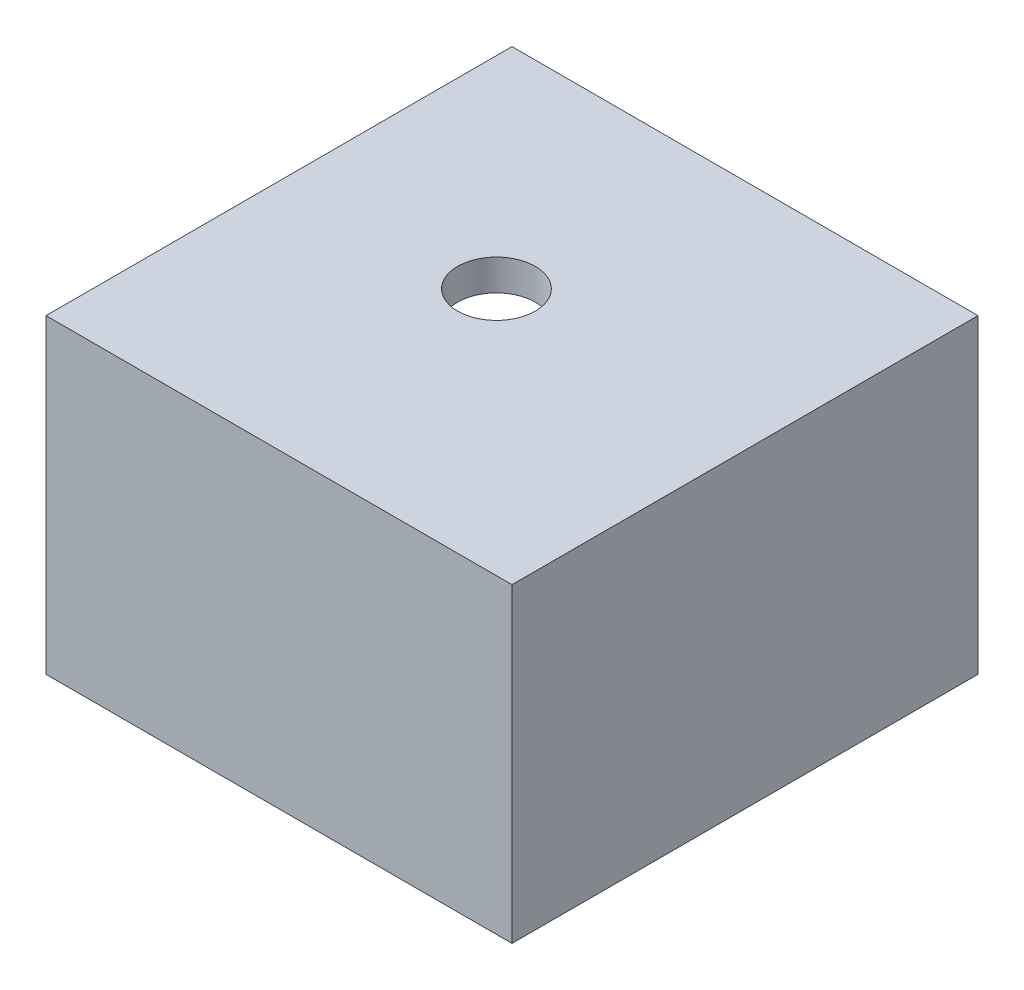
SolidWorks part; units mm, degrees
material "ABS PC"
ref_plane "Front Plane" through (0, 0, 0) normal (0, 0, 1) x (1, 0, 0)
ref_plane "Top Plane" through (0, 0, 0) normal (0, 1, 0) x (1, 0, 0)
ref_plane "Right Plane" through (0, 0, 0) normal (1, 0, 0) x (0, 0, -1)
sketch "Sketch1" plane through (0, 0, 0) normal (0, 1, 0) x (1, 0, 0)
  line L1 (15, -15) -> (-15, -15)
  line L2 (15, -15) -> (15, 15)
  line L3 (15, 15) -> (-15, 15)
  line L4 (-15, -15) -> (-15, 15)
  line L5 (15, -15) -> (-15, 15) construction
  line L6 (15, 15) -> (-15, -15) construction
  point P0 (0, 0)
  dimension "D1" = 30
extrude "Boss-Extrude1" add sketch "Sketch1" along normal mid plane 20
sketch "Sketch2" plane through (0, 0, 0) normal (0, 1, 0) x (1, 0, 0)
  line L0 (8, -8) -> (8, 23)
  line L1 (0, 0) -> (-15, 0)
  line L2 (0, 0) -> (0, 15)
  line L3 (0, 15) -> (-15, 15)
  line L4 (-15, 0) -> (-15, 15)
  line L5 (8, 23) -> (-23, 23)
  line L6 (-23, -8) -> (-23, 23)
  line L7 (8, -8) -> (-23, -8)
  dimension "D1" = 8
extrude "Cut-Extrude1" cut sketch "Sketch2" against normal mid plane 16
fillet "Fillet1" radius 1 1 edges at (8, 0, 8)
sketch "Sketch3" plane through (0, -8, 0) normal (0, 1, 0) x (1, 0, 0)
  circle A1 centre (-2, 1) radius 2.5
  dimension "D1" = 5
  dimension "D3" = 2
  dimension "D2" = 1
extrude "Cut-Extrude2" cut sketch "Sketch3" against normal through all both and the other way through all contours A1
